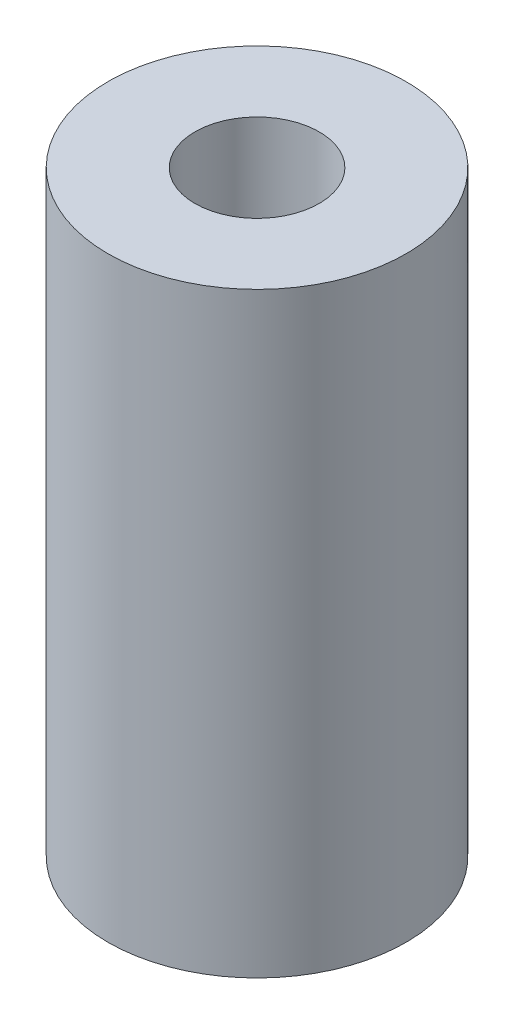
SolidWorks part; units mm, degrees
ref_plane "Спереди" through (0, 0, 0) normal (0, 0, 1) x (1, 0, 0)
ref_plane "Сверху" through (0, 0, 0) normal (0, 1, 0) x (1, 0, 0)
ref_plane "Справа" through (0, 0, 0) normal (1, 0, 0) x (0, 0, -1)
sketch "Эскиз1" plane through (0, 0, 0) normal (0, 1, 0) x (1, 0, 0)
  circle A0 centre (0, 0) radius 6
  dimension "D1" = 12
extrude "Бобышка-Вытянуть1" add sketch "Эскиз1" along normal blind 24
sketch "Эскиз2" plane through (0, 24, 0) normal (0, 1, 0) x (1, 0, 0)
  circle A0 centre (0, 0) radius 2.5
  dimension "D1" = 5
extrude "Вырез-Вытянуть1" cut sketch "Эскиз2" against normal blind 18
sketch "Эскиз3" plane through (0, 0, 0) normal (0, -1, 0) x (1, 0, 0)
  circle A0 centre (0, 0) radius 2.5
  dimension "D1" = 5
extrude "Вырез-Вытянуть2" cut sketch "Эскиз3" against normal blind 18
